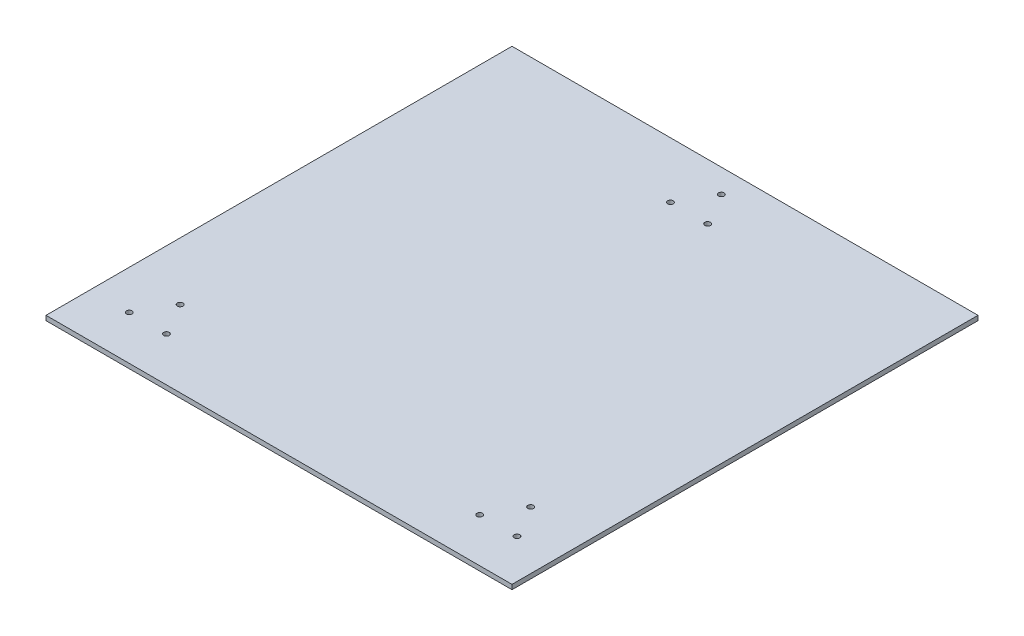
SolidWorks part; units mm, degrees
ref_plane "Спереди" through (0, 0, 0) normal (0, 0, 1) x (1, 0, 0)
ref_plane "Сверху" through (0, 0, 0) normal (0, 1, 0) x (1, 0, 0)
ref_plane "Справа" through (0, 0, 0) normal (1, 0, 0) x (0, 0, -1)
sketch "Эскиз1" plane through (0, 0, 0) normal (0, 1, 0) x (1, 0, 0)
  line L0 (125, 250) -> (125, 0) construction
  line L1 (0, 0) -> (250, 0)
  line L2 (0, 0) -> (0, 250)
  line L3 (0, 250) -> (250, 250)
  line L4 (250, 0) -> (250, 250)
  line L5 (125, 237.3) -> (125, 250) construction
  line L6 (115, 219.9795) -> (125, 237.3) construction
  line L7 (125, 237.3) -> (135, 219.9795) construction
  line L8 (135, 219.9795) -> (115, 219.9795) construction
  line L9 (125, 237.3) -> (195.5391, 237.3) construction
  line L10 (222.325, 46.7074) -> (305.9156, 191.4907) construction
  line L11 (44.0826, 18.2887) -> (-41.3283, 166.2247) construction
  line L12 (250, 125) -> (0, 125) construction
  line L13 (40.9812, 23.6605) -> (30.9812, 40.981) construction
  line L14 (20.9812, 23.6605) -> (30.9812, 40.981) construction
  line L15 (30.9812, 40.981) -> (40.9812, 23.6605) construction
  line L16 (40.9812, 23.6605) -> (20.9812, 23.6605) construction
  line L17 (219.0188, 40.981) -> (219.0188, 53.681) construction
  line L18 (209.0188, 23.6605) -> (219.0188, 40.981) construction
  line L19 (219.0188, 40.981) -> (229.0188, 23.6605) construction
  line L20 (229.0188, 23.6605) -> (209.0188, 23.6605) construction
  line L21 (230, 0) -> (219.0188, 6.34) construction
  line L22 (30.9812, 6.34) -> (20, 0) construction
  line L25 (30.9812, 6.34) -> (10.9812, 40.981) construction
  line L26 (10.9812, 40.981) -> (0, 34.641) construction
  line L27 (20, 0) -> (0, 34.641) construction
  line L28 (30.9812, 6.34) -> (0, 34.641) construction
  line L29 (10.9812, 40.981) -> (20, 0) construction
  line L30 (230, 0) -> (250, 34.641) construction
  line L31 (250, 34.641) -> (239.0188, 40.981) construction
  line L32 (219.0188, 6.34) -> (239.0188, 40.981) construction
  circle A0 centre (125, 237.3) radius 1.5
  circle A1 centre (135, 219.9795) radius 1.5
  circle A2 centre (115, 219.9795) radius 1.5
  circle A3 centre (30.9812, 40.981) radius 1.5
  circle A5 centre (40.9812, 23.6605) radius 1.5
  circle A6 centre (20.9812, 23.6605) radius 1.5
  circle A7 centre (219.0188, 40.981) radius 1.5
  circle A8 centre (229.0188, 23.6605) radius 1.5
  circle A9 centre (209.0188, 23.6605) radius 1.5
  point P23 (0, 0)
  point P25 (0, 0)
  point P26 (15.4906, 20.4905)
  point P41 (0, 0)
  point P42 (0, 0)
  point P43 (0, 0)
  point P44 (-23.2279, 1.3992)
  point P45 (-22.6011, 1.7259)
  point P46 (-16.2083, 2.9658)
  point P47 (0, 0)
  point P48 (0, 0)
  point P49 (0, 0)
  point P54 (0, 0)
  point P55 (0, 0)
  dimension "D3" = 3
  dimension "D8" = 3
  dimension "D14" = 3
  dimension "D1" = 250
  dimension "D2" = 250
  dimension "D4" = 12.7
  dimension "D5" = 20
  dimension "D6" = 60
  dimension "D7" = 60
  dimension "D9" = 20
  dimension "D10" = 12.7
  dimension "D11" = 20
  dimension "D12" = 40
  dimension "D13" = 12.68
  dimension "D16" = 90
  dimension "D17" = 12.68
  dimension "D18" = 40
  dimension "D19" = 90
extrude "Бобышка-Вытянуть1" add sketch "Эскиз1" along normal blind 2.5
